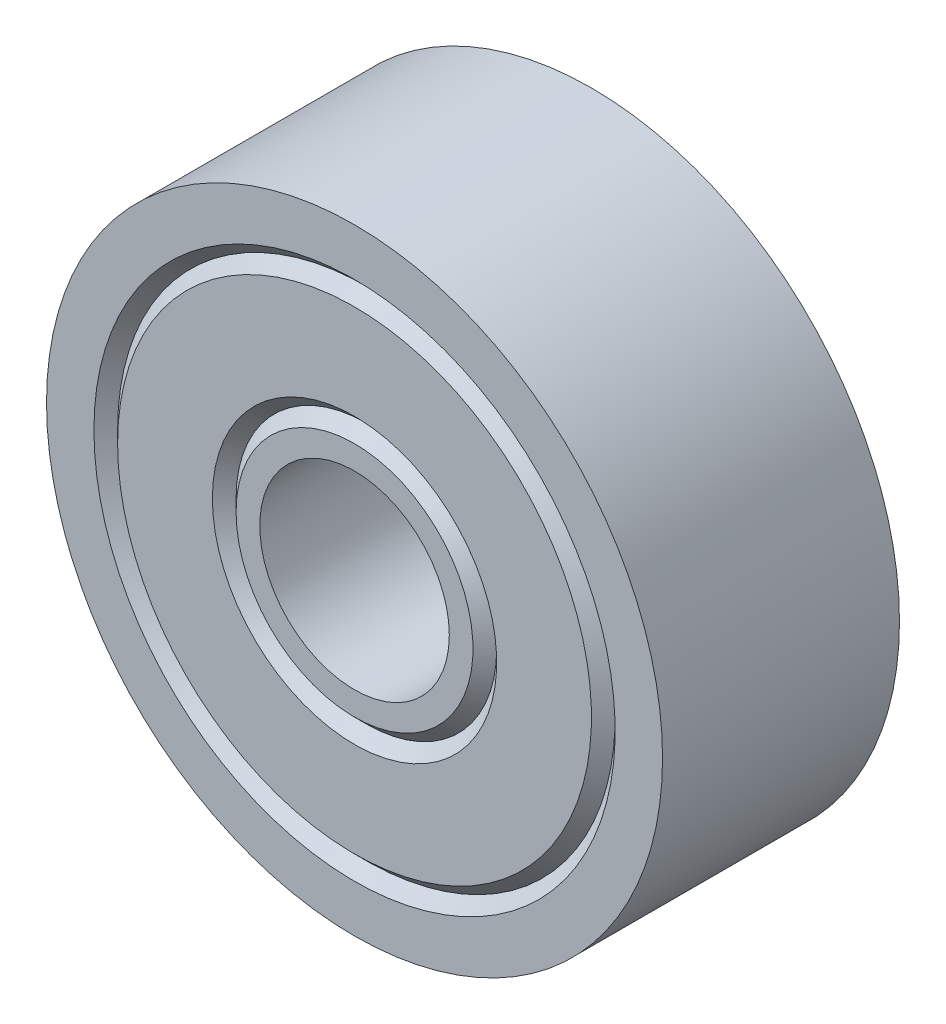
SolidWorks part; units mm, degrees
material "Plain Carbon Steel"
ref_plane "Front Plane" through (0, 0, 0) normal (0, 0, 1) x (1, 0, 0)
ref_plane "Top Plane" through (0, 0, 0) normal (0, 1, 0) x (1, 0, 0)
ref_plane "Right Plane" through (0, 0, 0) normal (1, 0, 0) x (0, 0, -1)
sketch "Sketch1" plane through (0, 0, 0) normal (0, 0, 1) x (1, 0, 0)
  circle A0 centre (0, 0) radius 2
  circle A1 centre (0, 0) radius 6.5
  dimension "D1" = 4
  dimension "D2" = 13
extrude "Boss-Extrude1" add sketch "Sketch1" along normal blind 5
sketch "Sketch2" plane through (0, 0, 0) normal (1, 0, 0) x (0, 0, -1)
  line L0 (-5, 5.5) -> (-5, 5)
  line L1 (-5, 6.5) -> (-5, -6.5) construction
  line L2 (-5, 5) -> (-4.75, 5.25)
  line L3 (-4.75, 5.25) -> (-5, 5.5)
  line L4 (-5, 3) -> (-5, 2.5)
  line L5 (-5, 2.5) -> (-4.75, 2.75)
  line L6 (-4.75, 2.75) -> (-5, 3)
  line L7 (0, 6.5) -> (-5, 6.5) construction
  line L8 (0, 0) -> (-5, 0) construction
  line L10 (-2.5, 0) -> (-2.5, 5.25) construction
  line L11 (-0.25, 2.75) -> (0, 3)
  line L12 (0, 2.5) -> (-0.25, 2.75)
  line L13 (0, 3) -> (0, 2.5)
  line L14 (-0.25, 5.25) -> (0, 5.5)
  line L15 (0, 5) -> (-0.25, 5.25)
  line L16 (0, 5.5) -> (0, 5)
  line L17 (-5, 2) -> (-5, -2) construction
  dimension "D1" = 1
  dimension "D2" = 0.25
  dimension "D3" = 2.5
revolve "Cut-Revolve1" cut sketch "Sketch2" angle 360 about L8
